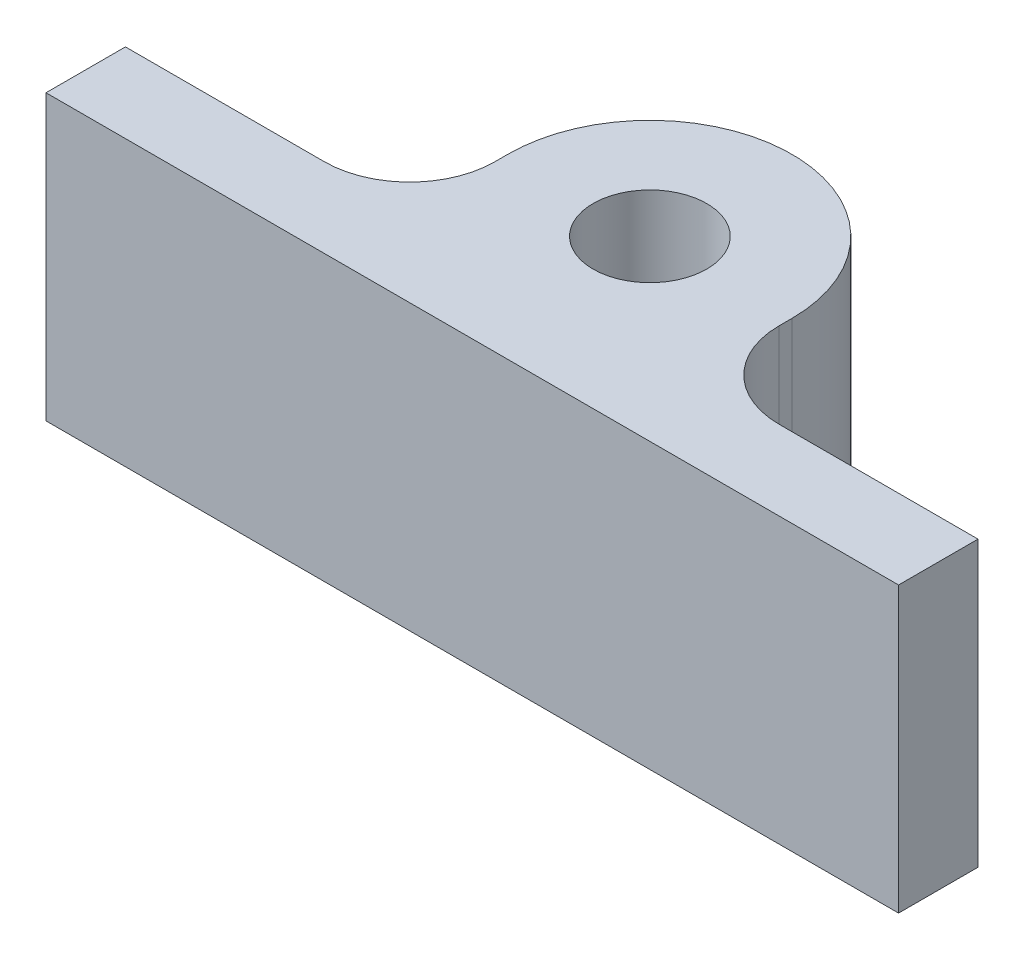
SolidWorks part; units mm, degrees
ref_plane "Front Plane" through (0, 0, 0) normal (0, 0, 1) x (1, 0, 0)
ref_plane "Top Plane" through (0, 0, 0) normal (0, 1, 0) x (1, 0, 0)
ref_plane "Right Plane" through (0, 0, 0) normal (1, 0, 0) x (0, 0, -1)
sketch "Sketch1" plane through (0, 0, 0) normal (0, 1, 0) x (1, 0, 0)
  line L0 (30, -12.5) -> (-30, -12.5)
  line L5 (-30, -12.5) -> (-30, -6.9096)
  line L7 (0, -47.9589) -> (0, -6.9096) construction
  line L8 (30, -12.5) -> (30, -6.9096)
  line L10 (-30, -6.9096) -> (-16, -6.9096)
  line L11 (-10, 0) -> (-10, -0.9096)
  line L12 (10, 0) -> (10, -0.9096)
  line L13 (16, -6.9096) -> (30, -6.9096)
  line L14 (0, -4) -> (0, 12.5) construction
  circle A0 centre (0, 0) radius 4
  arc A2 (10, 0) -> (-10, 0) centre (0, 0) ccw
  arc A3 (10, -0.9096) -> (16, -6.9096) centre (16, -0.9096) ccw
  arc A4 (-10, -0.9096) -> (-16, -6.9096) centre (-16, -0.9096) cw
  point P17 (10, -6.9096)
  dimension "D1" = 8
  dimension "D2" = 12.5
  dimension "D4" = 20
  dimension "D5" = 6
  dimension "D3" = 60
extrude "Boss-Extrude1" add sketch "Sketch1" along normal blind 20
